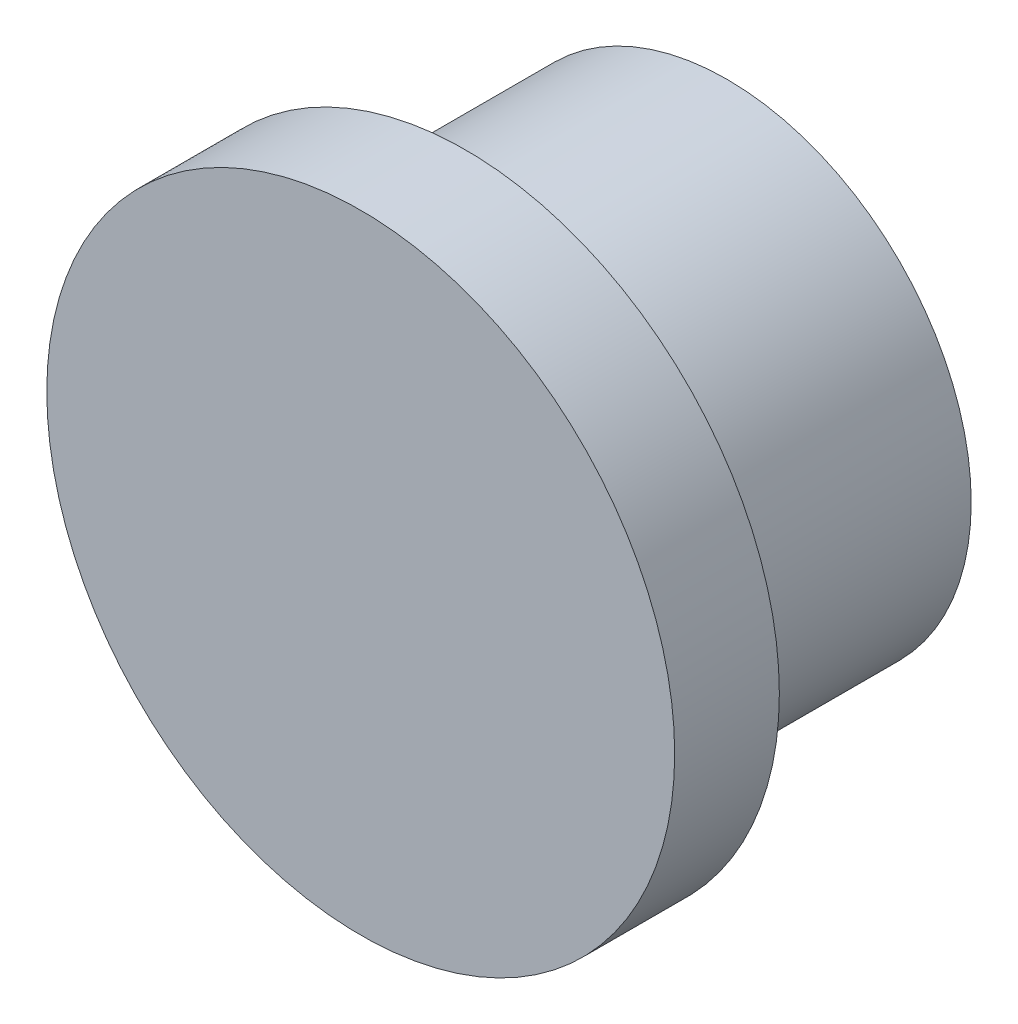
SolidWorks part; units mm, degrees
ref_plane "Alzado" through (0, 0, 0) normal (0, 0, 1) x (1, 0, 0)
ref_plane "Planta" through (0, 0, 0) normal (0, 1, 0) x (1, 0, 0)
ref_plane "Vista lateral" through (0, 0, 0) normal (1, 0, 0) x (0, 0, -1)
sketch "Croquis1" plane through (0, 0, 0) normal (0, 0, 1) x (1, 0, 0)
  circle A0 centre (-11.5252, -14.6911) radius 3.5
  dimension "D1" = 7
  dimension "D2" = 11.5252
  dimension "D3" = 14.6911
extrude "Saliente-Extruir1" add sketch "Croquis1" against normal blind 3.25 and the other way blind 1.75
sketch "Croquis2" plane through (0, 0, 1.75) normal (0, 0, 1) x (1, 0, 0)
  circle A0 centre (-11.5252, -14.6911) radius 4.5
  circle A1 centre (-11.5252, -14.6911) radius 3.5 construction
  dimension "D1" = 9
extrude "Saliente-Extruir2" add sketch "Croquis2" against normal blind 1.25 and the other way blind 0.25
